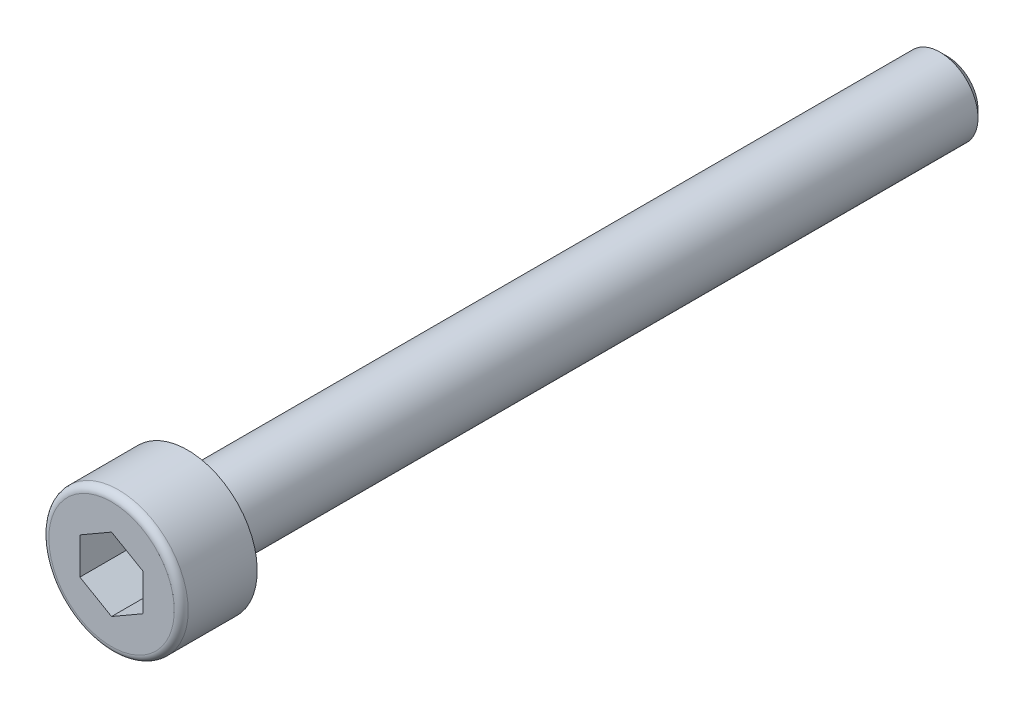
SolidWorks part; units mm, degrees
ref_plane "前视基准面" through (0, 0, 0) normal (0, 0, 1) x (1, 0, 0)
ref_plane "上视基准面" through (0, 0, 0) normal (0, 1, 0) x (1, 0, 0)
ref_plane "右视基准面" through (0, 0, 0) normal (1, 0, 0) x (0, 0, -1)
sketch "草图1" plane through (0, 0, 0) normal (1, 0, 0) x (0, 0, -1)
  line L0 (-3, 0) -> (30, 0) construction
  line L1 (-3, 0) -> (-3, 2.75)
  line L2 (-3, 2.75) -> (0, 2.75)
  line L3 (0, 2.75) -> (0, 1.5)
  line L4 (0, 1.5) -> (30, 1.5)
  line L5 (30, 1.5) -> (30, 0)
  point P3 (12, 1.5)
  dimension "A" = 5.5
  dimension "E" = 3
  dimension "L" = 30
  dimension "(e)" = 18
  dimension "M" = 3
sketch "草图2" plane through (0, 0, 0) normal (0, 0, 1) x (1, 0, 0)
  line L1 (0, 1.4434) -> (-1.25, 0.7217)
  line L2 (-1.25, 0.7217) -> (-1.25, -0.7217)
  line L3 (-1.25, -0.7217) -> (0, -1.4434)
  line L4 (0, -1.4434) -> (1.25, -0.7217)
  line L5 (1.25, -0.7217) -> (1.25, 0.7217)
  line L6 (1.25, 0.7217) -> (0, 1.4434)
  circle A0 centre (0, 0) radius 1.25 construction
  dimension "B" = 2.5
sketch "草图3" plane through (0, 0, 0) normal (1, 0, 0) x (0, 0, -1)
  line L0 (-3, 0) -> (-3, 2.75) construction
  line L1 (-3, 2.75) -> (0, 2.75) construction
  line L2 (0, 1.5) -> (30, 1.5) construction
  line L3 (0, 2.75) -> (0, 1.5) construction
  line L4 (-3, 0) -> (30, 0) construction
  line L5 (30, 1.5) -> (30, 0) construction
  line L6 (-3, 0) -> (-3, 2.75)
  line L7 (-3, 2.75) -> (0, 2.75)
  line L8 (0, 1.5) -> (30, 1.5)
  line L9 (0, 2.75) -> (0, 1.5)
  line L10 (-3, 0) -> (30, 0)
  line L11 (30, 1.5) -> (30, 0)
revolve "旋转1" add sketch "草图3" angle 360 about L10
cosmetic thread "装饰螺纹线1" parameters "D1"=18, "D2"=2.55
sketch "草图4" plane through (0, 0, 3) normal (0, 0, 1) x (1, 0, 0)
  line L0 (0, 1.4434) -> (-1.25, 0.7217) construction
  line L1 (-1.25, 0.7217) -> (-1.25, -0.7217) construction
  line L2 (-1.25, -0.7217) -> (0, -1.4434) construction
  line L3 (0, -1.4434) -> (1.25, -0.7217) construction
  line L4 (1.25, -0.7217) -> (1.25, 0.7217) construction
  line L5 (1.25, 0.7217) -> (0, 1.4434) construction
  line L6 (0, 1.4434) -> (-1.25, 0.7217)
  line L7 (-1.25, 0.7217) -> (-1.25, -0.7217)
  line L8 (-1.25, -0.7217) -> (0, -1.4434)
  line L9 (0, -1.4434) -> (1.25, -0.7217)
  line L10 (1.25, -0.7217) -> (1.25, 0.7217)
  line L11 (1.25, 0.7217) -> (0, 1.4434)
extrude "切除-拉伸1" cut sketch "草图4" against normal blind 1.925
fillet "圆角1" radius 0.275 1 edges at (0, -2.75, 3)
chamfer "倒角1" distance 0.3 angle 45 1 edges at (0, -1.5, -30)
